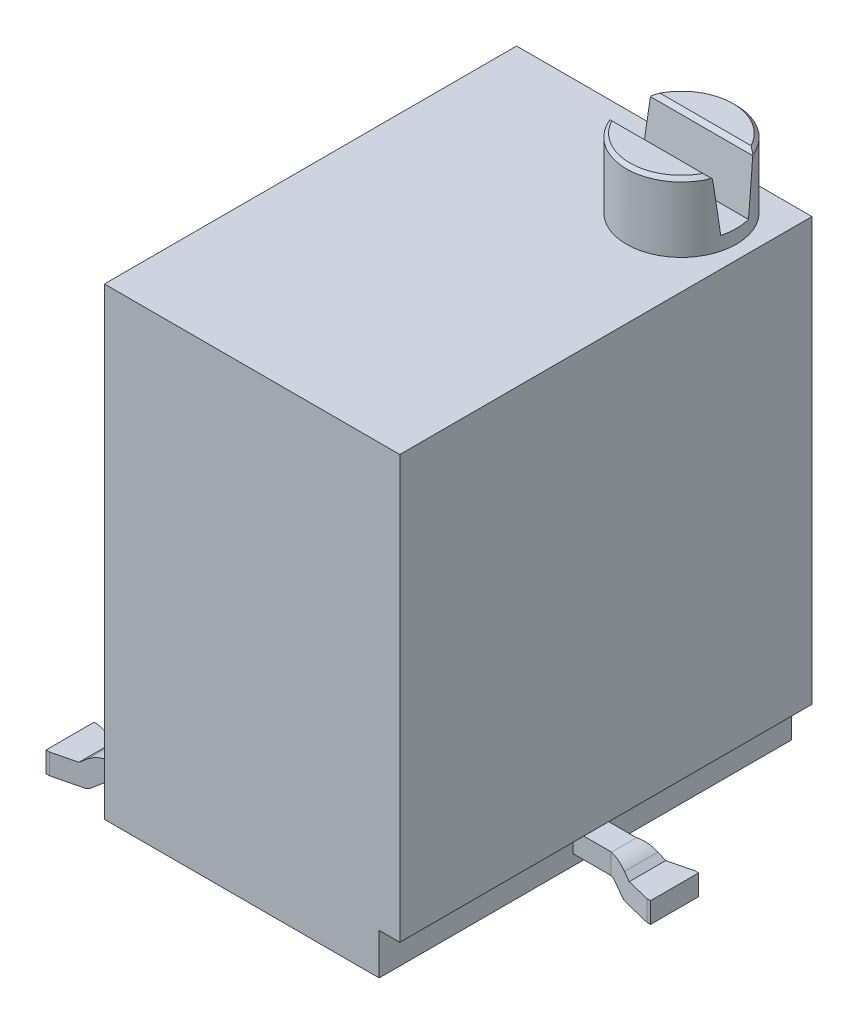
SolidWorks part; units mm, degrees
ref_plane "Front Plane" through (0, 0, 0) normal (0, 0, 1) x (1, 0, 0)
ref_plane "Top Plane" through (0, 0, 0) normal (0, 1, 0) x (1, 0, 0)
ref_plane "Right Plane" through (0, 0, 0) normal (1, 0, 0) x (0, 0, -1)
sketch "Sketch1" plane through (0, 0, 0) normal (0, 1, 0) x (1, 0, 0)
  line L0 (2.15, -3) -> (2.15, 3)
  line L1 (0, 0) -> (-2.15, 0) construction
  line L2 (0, 0) -> (0, 3) construction
  line L3 (2.15, 3) -> (-2.15, 3)
  line L4 (-2.15, -3) -> (-2.15, 3)
  line L5 (2.15, -3) -> (-2.15, -3)
  point P8 (2.15, 0)
  dimension "D1" = 2.15
  dimension "D2" = 3
extrude "Boss-Extrude1" add sketch "Sketch1" along normal blind 6.75
sketch "Sketch2" plane through (0, 6.75, 0) normal (0, 1, 0) x (1, 0, 0)
  circle A0 centre (1.15, 2.1) radius 0.8
extrude "Boss-Extrude2" add sketch "Sketch2" along normal blind 1
sketch "Sketch3" plane through (0, 7.75, 0) normal (0, 1, 0) x (1, 0, 0)
  line L0 (-1.9934, 2.1) -> (1.15, 2.1) construction
  line L1 (2.056, 2.4) -> (0.244, 2.4)
  line L2 (2.056, 1.8) -> (0.244, 1.8)
  line L3 (0.244, 2.4) -> (0.244, 1.8)
  line L4 (2.056, 2.4) -> (2.056, 1.8)
  dimension "D1" = 0.3
extrude "Cut-Extrude2" cut sketch "Sketch3" against normal blind 0.8 draft 7
chamfer "Chamfer1" distance 0.05 angle 45 4 edges at (1.15, 7.75, -2.4) (1.15, 7.75, -1.8) (1.15, 7.75, -1.3) (1.15, 7.75, -2.9)
sketch "Sketch6" plane through (0, 0, 3) normal (0, 0, 1) x (1, 0, 0)
  line L0 (-2.15, 0.1602) -> (-2.4149, 0.1602)
  line L2 (-2.4774, 0.1382) -> (-2.6226, 0.0219)
  line L4 (-2.6851, 0) -> (-3.15, 0)
  line L5 (-2.15, 0.4602) -> (-2.4149, 0.4602)
  line L6 (-2.6649, 0.3724) -> (-2.7553, 0.3)
  line L7 (-2.7553, 0.3) -> (-3.15, 0.3)
  line L8 (-3.15, 0.3) -> (-3.15, 0)
  line L9 (-2.15, 0.4602) -> (-2.15, 0.1602)
  arc A0 (-2.6226, 0.0219) -> (-2.6851, 0) centre (-2.6851, 0.1) cw
  arc A1 (-2.4774, 0.1382) -> (-2.4149, 0.1602) centre (-2.4149, 0.0602) cw
  arc A2 (-2.6649, 0.3724) -> (-2.4149, 0.4602) centre (-2.4149, 0.0602) cw
  point P10 (-2.65, 0)
  point P13 (-2.45, 0.1602)
  dimension "D5" = 0.1
  dimension "D1" = 141.311
extrude "Boss-Extrude3" add sketch "Sketch6" against normal through all separate body
mirror "Mirror8" about plane through (0, 0, 0) normal (1, 0, 0) of "Boss-Extrude3"
sketch "Sketch7" plane through (0, 0, 0) normal (0, -1, 0) x (1, 0, 0)
  line L0 (0, 0) -> (-3.15, 0) construction
  line L1 (-3.15, -3) -> (-3.15, 3) construction
  line L2 (-2.15, 2.5) -> (-3.15, 2.5) construction
  line L3 (-3.098, 2.85) -> (-3.15, 2.85)
  line L4 (-3.098, 2.15) -> (-3.15, 2.15)
  line L5 (-2.15, 2.6813) -> (-2.4076, 2.6813)
  line L6 (-2.15, 2.3187) -> (-2.4076, 2.3187)
  line L7 (-2.4076, 2.6813) -> (-3.098, 2.85)
  line L9 (-2.4076, 2.3187) -> (-3.098, 2.15)
  line L10 (-2.15, -2.6813) -> (-2.15, -3)
  line L11 (-3.15, 2.85) -> (-3.15, 3)
  line L12 (-3.15, 3) -> (-2.15, 3)
  line L13 (-2.15, 3) -> (-2.15, 2.6813)
  line L14 (-2.15, -2.5) -> (-3.15, -2.5) construction
  line L15 (-2.15, -3) -> (-2.15, 3) construction
  line L16 (-2.15, -3) -> (-3.15, -3)
  line L17 (-2.4076, -2.3187) -> (-3.098, -2.15)
  line L18 (-2.4076, -2.6813) -> (-3.098, -2.85)
  line L19 (-2.15, -2.3187) -> (-2.4076, -2.3187)
  line L20 (-2.15, -2.6813) -> (-2.4076, -2.6813)
  line L21 (-3.098, -2.15) -> (-3.15, -2.15)
  line L22 (-3.098, -2.85) -> (-3.15, -2.85)
  line L23 (-3.15, 2.15) -> (-3.15, -2.15)
  line L24 (-2.15, -2.3187) -> (-2.15, 2.3187)
  line L25 (-3.15, -3) -> (-3.15, -2.85)
  line L33 (0, 0) -> (0, 3) construction
  line L34 (-2.15, 3) -> (2.15, 3) construction
  line L41 (2.15, 0) -> (3.15, 0) construction
  line L42 (2.15, 0.1813) -> (2.4076, 0.1813)
  line L43 (3.098, 0.35) -> (3.15, 0.35)
  line L44 (2.4076, 0.1813) -> (3.098, 0.35)
  line L45 (2.15, -0.1813) -> (2.4076, -0.1813)
  line L46 (3.098, -0.35) -> (3.15, -0.35)
  line L47 (2.4076, -0.1813) -> (3.098, -0.35)
  line L48 (2.4076, 0.1813) -> (3.098, 0.35)
  line L49 (3.098, 0.35) -> (3.15, 0.35)
  line L50 (2.15, 0.1813) -> (2.4076, 0.1813)
  line L51 (2.4076, -0.1813) -> (3.098, -0.35)
  line L52 (3.098, -0.35) -> (3.15, -0.35)
  line L53 (2.15, -0.1813) -> (2.4076, -0.1813)
  line L54 (2.15, 0.1813) -> (2.15, 3)
  line L55 (2.15, 3) -> (3.15, 3)
  line L56 (3.15, 3) -> (3.15, 0.35)
  line L57 (2.15, -0.1813) -> (2.15, -3)
  line L58 (2.15, -3) -> (3.15, -3)
  line L59 (3.15, -3) -> (3.15, -0.35)
  point P5 (0, 2.5)
  point P7 (0, 2.85)
  point P9 (0, 2.15)
  point P11 (0, 2.75)
  point P12 (-3.15, 2.75)
  point P13 (0, 2.25)
  point P14 (-3.15, 2.25)
  line M1 (-2.15, 3) -> (-2.15, -3)
  line M3 (2.15, -3) -> (2.15, 3)
extrude "Cut-Extrude5" cut sketch "Sketch7" against normal blind 0.8 contours L4 L23 L21 L17 L19 L6 L9 M1 | L12 L11 L3 L7 L5 M1 | L25 L16 L20 L18 L22 M1 | L58 L59 L46 L47 L45 M3 | L56 L55 L42 L44 L43 M3
sketch "Sketch8" plane through (-2.15, 0, 0) normal (-1, 0, 0) x (0, 0, 1)
  line L14 (2.85, 0.15) -> (2.85, 6.6)
  line L15 (-2.85, 0.15) -> (2.85, 0.15)
  line L16 (-2.85, 6.6) -> (-2.85, 0.15)
  line L17 (2.85, 6.6) -> (-2.85, 6.6)
  line L18 (2.85, 0.15) -> (2.85, 6.6)
  line L19 (-2.85, 0.15) -> (2.85, 0.15)
  line L20 (-2.85, 6.6) -> (-2.85, 0.15)
  line L21 (2.85, 6.6) -> (-2.85, 6.6)
  dimension "D1" = 0.15
split line "Split Line1"
sketch "Sketch9" plane through (0, 0, 3) normal (0, 0, 1) x (1, 0, 0)
  line L1 (2.15, 0) -> (1.85, 0)
  line L2 (2.15, 0) -> (2.15, 0.6)
  line L3 (2.15, 0.6) -> (1.85, 0.6)
  line L4 (1.85, 0) -> (1.85, 0.6)
  dimension "D1" = 0.3
  dimension "D2" = 0.6
extrude "Cut-Extrude7" cut sketch "Sketch9" against normal through all
sketch "Sketch10" plane through (2.15, 0, 0) normal (-1, 0, 0) x (0, 0, 1)
  line L4 (0.1813, 0.4602) -> (-0.1813, 0.4602)
  line L5 (-0.1813, 0.4602) -> (-0.1813, 0.1602)
  line L6 (-0.1813, 0.1602) -> (0.1813, 0.1602)
  line L7 (0.1813, 0.1602) -> (0.1813, 0.4602)
  line L8 (0.1813, 0.4602) -> (-0.1813, 0.4602)
  line L9 (-0.1813, 0.4602) -> (-0.1813, 0.1602)
  line L10 (-0.1813, 0.1602) -> (0.1813, 0.1602)
  line L11 (0.1813, 0.1602) -> (0.1813, 0.4602)
  dimension "D1" = 0
extrude "Boss-Extrude4" add sketch "Sketch10" along normal up to surface (0.3 mm away) up to face at (1.85, 0.3, 0)
